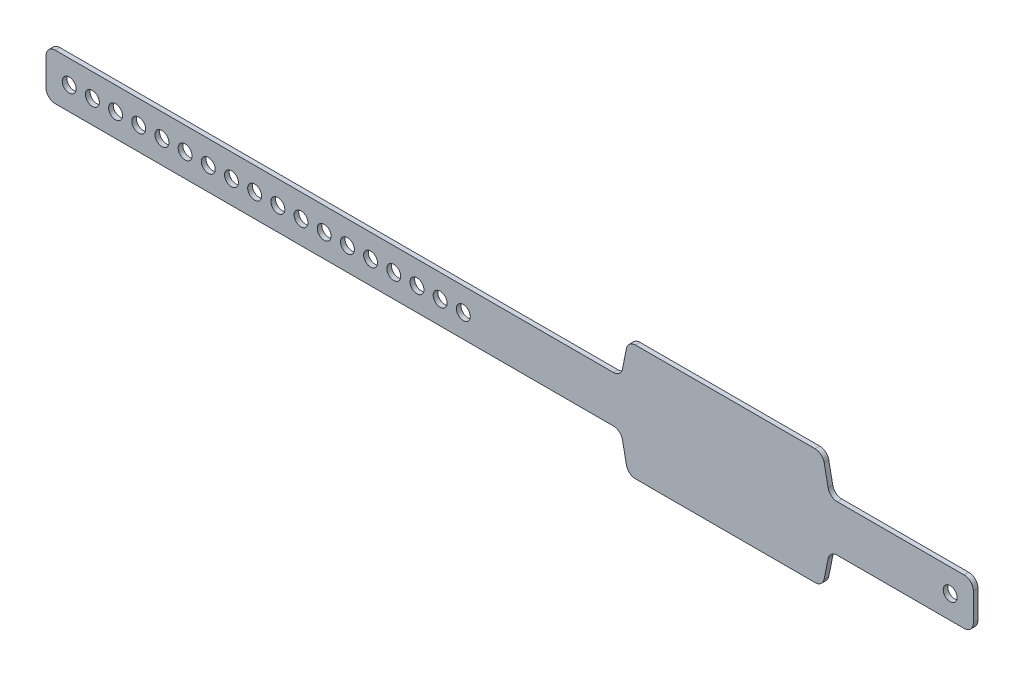
SolidWorks part; units mm, degrees
ref_plane "Front Plane" through (0, 0, 0) normal (0, 0, 1) x (1, 0, 0)
ref_plane "Top Plane" through (0, 0, 0) normal (0, 1, 0) x (1, 0, 0)
ref_plane "Right Plane" through (0, 0, 0) normal (1, 0, 0) x (0, 0, -1)
sketch "Sketch2" plane through (0, 0, 0) normal (0, 0, 1) x (1, 0, 0)
  line L1 (2, 0) -> (198, 0)
  line L2 (0, 2) -> (0, 8)
  line L3 (2, 10) -> (198, 10)
  line L4 (200, 2) -> (200, 8)
  arc A0 (198, 0) -> (200, 2) centre (198, 2) ccw
  arc A1 (198, 10) -> (200, 8) centre (198, 8) cw
  arc A2 (2, 0) -> (0, 2) centre (2, 2) cw
  arc A3 (0, 8) -> (2, 10) centre (2, 8) cw
  point P9 (200, 10)
  point P12 (0, 0)
  point P15 (0, 10)
  dimension "D3" = 2
  dimension "D1" = 200
  dimension "D2" = 10
extrude "Boss-Extrude1" add sketch "Sketch2" along normal blind 1
sketch "Sketch3" plane through (0, 0, 0) normal (0, 0, -1) x (-1, 0, 0)
  line L0 (-124, 0) -> (-125.1784, -5.8922)
  line L1 (-2, 0) -> (-198, 0) construction
  line L2 (-127.1396, -7.5) -> (-165.8604, -7.5)
  line L3 (-167.8216, -5.8922) -> (-169, 0)
  line L4 (-169, 0) -> (-124, 0)
  line L5 (0, 5) -> (-200, 5) construction
  line L6 (0, 8) -> (0, 2) construction
  line L7 (-200, 2) -> (-200, 8) construction
  line L8 (-169, 10) -> (-124, 10)
  line L9 (-167.8216, 15.8922) -> (-169, 10)
  line L10 (-127.1396, 17.5) -> (-165.8604, 17.5)
  line L11 (-124, 10) -> (-125.1784, 15.8922)
  arc A0 (-125.1784, -5.8922) -> (-127.1396, -7.5) centre (-127.1396, -5.5) cw
  arc A1 (-165.8604, -7.5) -> (-167.8216, -5.8922) centre (-165.8604, -5.5) cw
  arc A2 (-165.8604, 17.5) -> (-167.8216, 15.8922) centre (-165.8604, 15.5) ccw
  arc A3 (-125.1784, 15.8922) -> (-127.1396, 17.5) centre (-127.1396, 15.5) ccw
  point P16 (-125.5, -7.5)
  point P19 (-167.5, -7.5)
  point P28 (-167.5, 17.5)
  point P29 (-125.5, 17.5)
  dimension "D6" = 2
  dimension "D1" = 45
  dimension "D2" = 42
  dimension "D3" = 124
  dimension "D4" = 7.5
  dimension "D5" = 1.5
extrude "Boss-Extrude2" add sketch "Sketch3" against normal blind 1
fillet "Fillet1" radius 2 4 edges at (169, 0, 0.5) (169, 10, 0.5) (124, 0, 0.5) (124, 10, 0.5)
sketch "Sketch4" plane through (0, 0, 0) normal (0, 0, -1) x (-1, 0, 0)
  line L0 (-200, 2) -> (-200, 8) construction
  line L2 (0, 8) -> (0, 2) construction
  circle A0 centre (-5, 5) radius 1.5
  circle A1 centre (-10, 5) radius 1.5
  circle A2 centre (-15, 5) radius 1.5
  circle A3 centre (-20, 5) radius 1.5
  circle A5 centre (-25, 5) radius 1.5
  circle A6 centre (-30, 5) radius 1.5
  circle A7 centre (-195, 5) radius 1.5
  circle A8 centre (-35, 5) radius 1.5
  circle A9 centre (-40, 5) radius 1.5
  circle A10 centre (-45, 5) radius 1.5
  circle A11 centre (-50, 5) radius 1.5
  circle A12 centre (-55, 5) radius 1.5
  circle A13 centre (-60, 5) radius 1.5
  circle A14 centre (-65, 5) radius 1.5
  circle A15 centre (-70, 5) radius 1.5
  circle A16 centre (-75, 5) radius 1.5
  circle A17 centre (-80, 5) radius 1.5
  circle A18 centre (-85, 5) radius 1.5
  circle A19 centre (-90, 5) radius 1.5
  point P5 (0, 5)
  point P19 (-200, 5)
  dimension "D1" = 3
  dimension "D4" = 5
  dimension "D5" = 3
  dimension "D6" = 5
  dimension "D2" = 5
  dimension "D3" = 18
extrude "Cut-Extrude1" cut sketch "Sketch4" against normal through all
ref_plane "Plane1" through (100, 0, 0) normal (-1, 0, 0) x (0, 0, 1)
